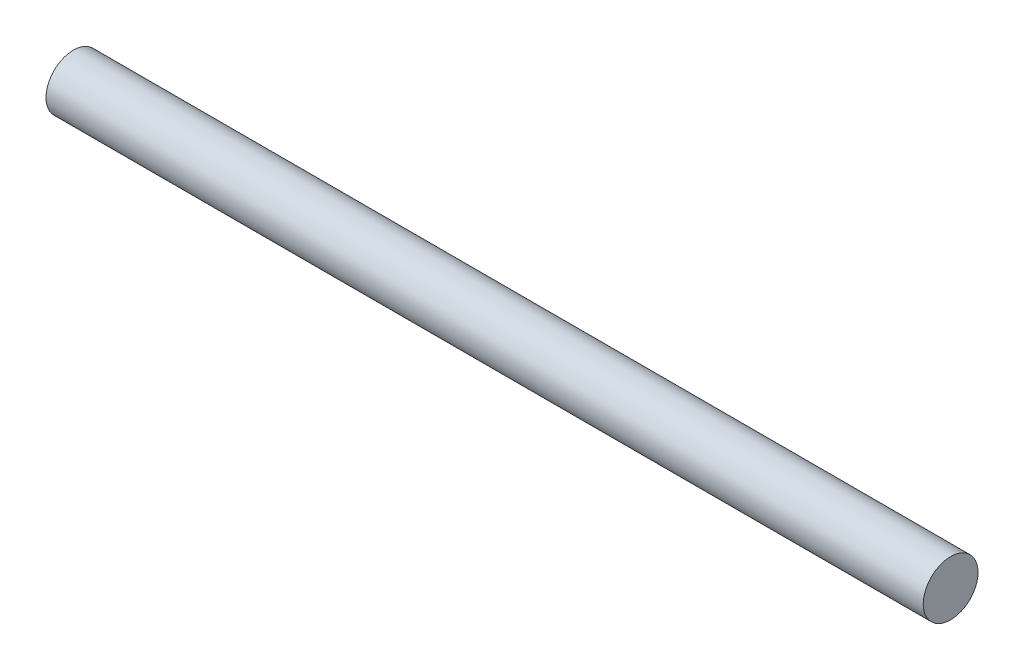
SolidWorks part; units mm, degrees
ref_plane "Front Plane" through (0, 0, 0) normal (0, 0, 1) x (1, 0, 0)
ref_plane "Top Plane" through (0, 0, 0) normal (0, 1, 0) x (1, 0, 0)
ref_plane "Right Plane" through (0, 0, 0) normal (1, 0, 0) x (0, 0, -1)
sketch "Sketch1" plane through (0, 0, 0) normal (1, 0, 0) x (0, 0, -1)
  circle A0 centre (0, 0) radius 19.05
  dimension "D1" = 38.1
extrude "Boss-Extrude1" add sketch "Sketch1" along normal mid plane 609.6
